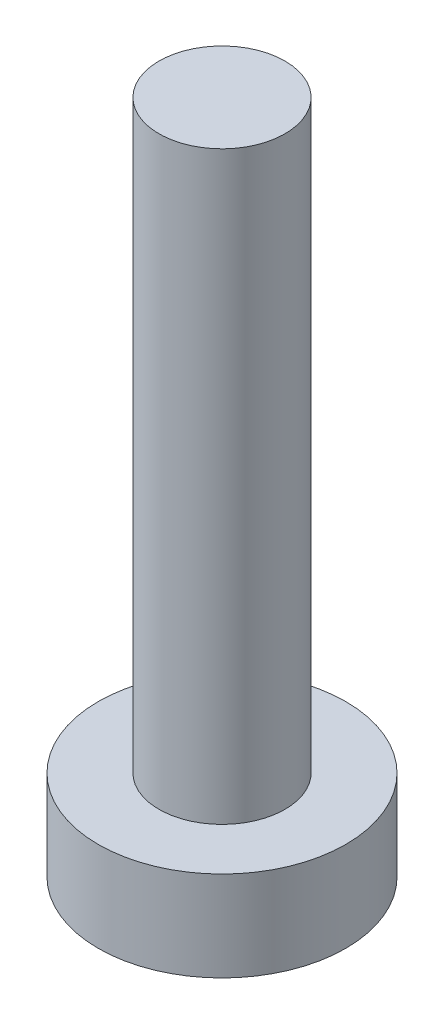
SolidWorks part; units mm, degrees
ref_plane "Front Plane" through (0, 0, 0) normal (0, 0, 1) x (1, 0, 0)
ref_plane "Top Plane" through (0, 0, 0) normal (0, 1, 0) x (1, 0, 0)
ref_plane "Right Plane" through (0, 0, 0) normal (1, 0, 0) x (0, 0, -1)
sketch "Sketch2" plane through (0, 0, 0) normal (0, 1, 0) x (1, 0, 0)
  circle A0 centre (0, 0) radius 2.75
  dimension "D1" = 5.5
extrude "Boss-Extrude1" add sketch "Sketch2" along normal blind 2
sketch "Sketch3" plane through (0, 2, 0) normal (0, 1, 0) x (1, 0, 0)
  circle A0 centre (0, 0) radius 1.4
  dimension "D1" = 2.8
extrude "Boss-Extrude2" add sketch "Sketch3" along normal blind 13
sketch "Sketch4" plane through (0, 0, 0) normal (0, -1, 0) x (1, 0, 0)
  line L1 (1.1547, 0) -> (0.5774, 1)
  line L2 (0.5774, 1) -> (-0.5774, 1)
  line L3 (-0.5774, 1) -> (-1.1547, 0)
  line L4 (-1.1547, 0) -> (-0.5774, -1)
  line L5 (-0.5774, -1) -> (0.5774, -1)
  line L6 (0.5774, -1) -> (1.1547, 0)
  circle A0 centre (0, 0) radius 1 construction
  dimension "D1" = 2
extrude "Cut-Extrude1" cut sketch "Sketch4" against normal blind 1.5
equation "\"Length\"=13"
equation "\"D1@Boss-Extrude2\"=\"Length\""
